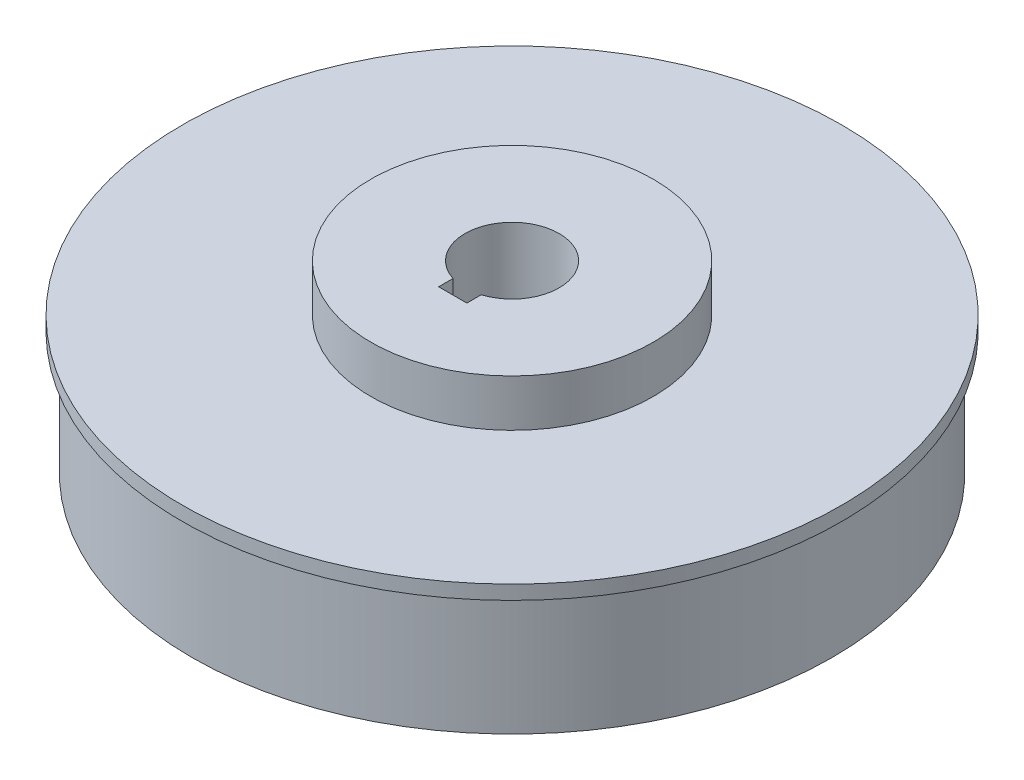
SolidWorks part; units mm, degrees
ref_plane "Front" through (0, 0, 0) normal (0, 0, 1) x (1, 0, 0)
ref_plane "Top" through (0, 0, 0) normal (0, 1, 0) x (1, 0, 0)
ref_plane "Right" through (0, 0, 0) normal (1, 0, 0) x (0, 0, -1)
sketch "Sketch1" plane through (0, 0, 0) normal (0, 0, 1) x (1, 0, 0)
  line L4 (34, 14.5) -> (34, 1.5)
  line L9 (0, 0) -> (0, 21)
  line L14 (34, 14.5) -> (35, 14.5)
  line L15 (35, 14.5) -> (35, 16)
  line L16 (35, 16) -> (15, 16)
  line L17 (15, 16) -> (15, 21)
  line L18 (15, 21) -> (0, 21)
  line L19 (34, 1.5) -> (24, 1.5)
  line L20 (24, 1.5) -> (24, 0)
  line L21 (24, 0) -> (0, 0)
  dimension "D1" = 21
  dimension "D2" = 34
  dimension "D3" = 13
  dimension "D4" = 1.5
  dimension "D5" = 15
  dimension "D6" = 35
  dimension "D7" = 1.5
revolve "Revolve2" add sketch "Sketch1" angle 360 about L9
sketch "Sketch2" plane through (0, 21, 0) normal (0, 1, 0) x (1, 0, 0)
  circle A2 centre (0, 0) radius 5
  dimension "D1" = 10
sketch "Sketch3" plane through (0, 21, 0) normal (0, 1, 0) x (1, 0, 0)
  line L5 (-1.5, -4.3) -> (1.5, -4.3)
  line L6 (-1.5, -4.3) -> (-1.5, -6.3)
  line L7 (-1.5, -6.3) -> (1.5, -6.3)
  line L8 (1.5, -4.3) -> (1.5, -6.3)
  line L9 (-1.5, -4.3) -> (1.5, -6.3) construction
  line L10 (-1.5, -6.3) -> (1.5, -4.3) construction
  point P11 (0, -5.3)
  dimension "D3" = 6.3
  dimension "D4" = 3
  dimension "D5" = 1.5
  dimension "D6" = 2
extrude "Cut-Extrude1" cut sketch "Sketch2" against normal through all
extrude "Cut-Extrude2" cut sketch "Sketch3" against normal through all
sketch "Sketch4" plane through (0, 21, 0) normal (0, 1, 0) x (1, 0, 0)
  line L0 (0, 0) -> (0, 40.6715) construction
